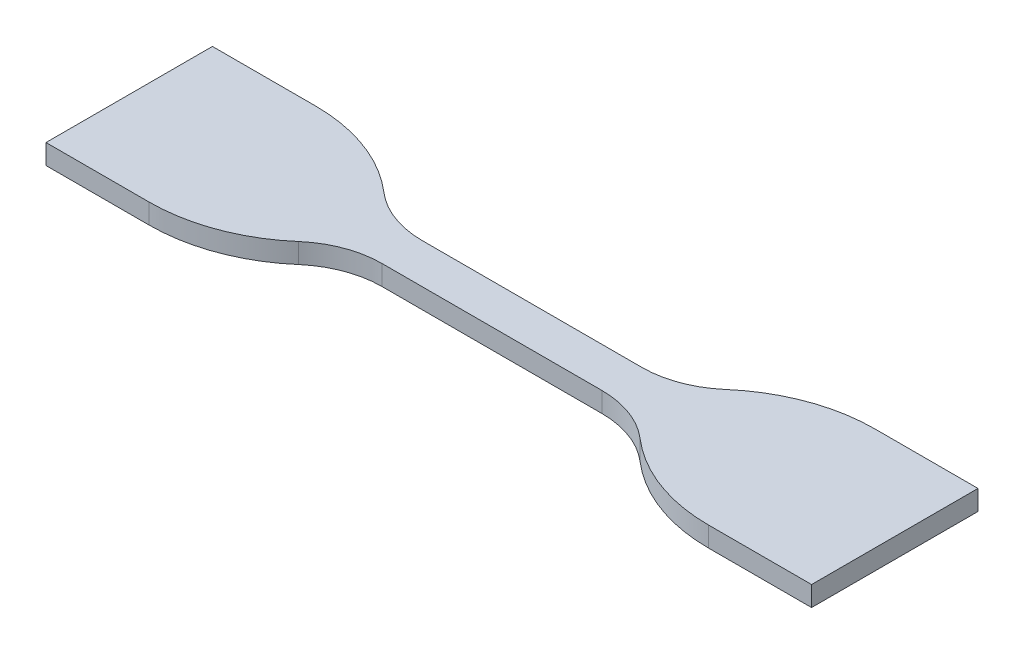
SolidWorks part; units mm, degrees
material "SUV Elastomer"
ref_plane "Front Plane" through (0, 0, 0) normal (0, 0, 1) x (1, 0, 0)
ref_plane "Top Plane" through (0, 0, 0) normal (0, 1, 0) x (1, 0, 0)
ref_plane "Right Plane" through (0, 0, 0) normal (1, 0, 0) x (0, 0, -1)
sketch "Sketch3" plane through (0, 0, 0) normal (0, 1, 0) x (1, 0, 0)
  line L0 (0, 0) -> (-15.4902, 0)
  line L1 (-15.4902, 0) -> (-15.4902, 25)
  line L2 (-15.4902, 25) -> (0, 25)
  line L3 (25.5098, 15.5) -> (58.5098, 15.5)
  line L4 (25.5098, 9.5) -> (58.5098, 9.5)
  line L5 (42.0098, 15.5) -> (42.0098, 9.5)
  line L6 (99.5098, 25) -> (84.0196, 25)
  line L7 (99.5098, 0) -> (99.5098, 25)
  line L8 (84.0196, 0) -> (99.5098, 0)
  arc A0 (0, 25) -> (16.3524, 18.9103) centre (0, 0) cw
  arc A1 (16.3524, 18.9103) -> (25.5098, 15.5) centre (25.5098, 29.5) ccw
  arc A2 (0, 0) -> (16.3524, 6.0897) centre (0, 25) ccw
  arc A3 (16.3524, 6.0897) -> (25.5098, 9.5) centre (25.5098, -4.5) cw
  arc A4 (67.6672, 6.0897) -> (58.5098, 9.5) centre (58.5098, -4.5) ccw
  arc A5 (84.0196, 0) -> (67.6672, 6.0897) centre (84.0196, 25) cw
  arc A6 (67.6672, 18.9103) -> (58.5098, 15.5) centre (58.5098, 29.5) cw
  arc A7 (84.0196, 25) -> (67.6672, 18.9103) centre (84.0196, 0) ccw
  dimension "D4" = 25
  dimension "D5" = 14
  dimension "D6" = 6
  dimension "D1" = 115
  dimension "D2" = 25
  dimension "D3" = 33
extrude "Boss-Extrude1" add sketch "Sketch3" along normal blind 3 contours L4 A4 A5 L8 L7 L6 A7 A6 L3 A1 A0 L2 L1 L0 A2 A3
